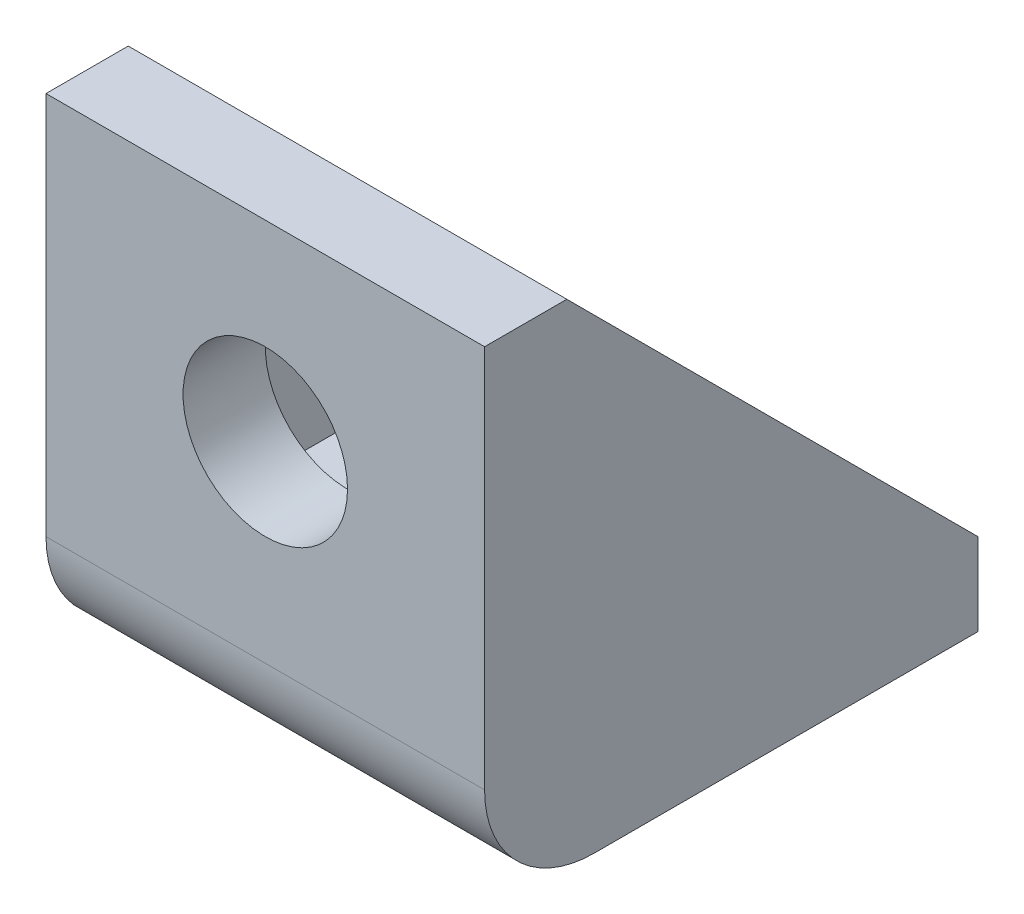
SolidWorks part; units mm, degrees
ref_plane "Front Plane" through (0, 0, 0) normal (0, 0, 1) x (1, 0, 0)
ref_plane "Top Plane" through (0, 0, 0) normal (0, 1, 0) x (1, 0, 0)
ref_plane "Right Plane" through (0, 0, 0) normal (1, 0, 0) x (0, 0, -1)
sketch "Sketch1" plane through (0, 0, 0) normal (1, 0, 0) x (0, 0, -1)
  line L1 (0, 0) -> (9, 0)
  line L2 (0, 0) -> (0, 1.6648)
  line L3 (1.5, 1.5) -> (9, 1.5)
  line L4 (9, 0) -> (9, 1.5)
  line L5 (0, 0) -> (1.7521, 0)
  line L6 (0, 0) -> (0, 9)
  line L7 (0, 9) -> (1.5, 9)
  line L8 (1.5, 1.5) -> (1.5, 9)
  dimension "D1" = 9
  dimension "D2" = 7.5
  dimension "D3" = 1.5
extrude "Boss-Extrude1" add sketch "Sketch1" along normal mid plane 8 contours L3 L8 L7 L6 L2 L1 L4
sketch "Sketch2" plane through (4, 0, 0) normal (1, 0, 0) x (0, 0, -1)
  line L0 (1.5, 9) -> (9, 1.5)
  line L1 (1.5, 1.5) -> (9, 1.5) construction
  line L2 (1.5, 1.5) -> (1.5, 9) construction
  line L3 (1.5, 1.5) -> (9, 1.5)
  line L4 (1.5, 1.5) -> (1.5, 9)
extrude "Boss-Extrude2" add sketch "Sketch2" against normal blind 0.5
mirror "Mirror1" about plane through (0, 0, 0) normal (1, 0, 0) of "Boss-Extrude2"
sketch "Sketch3" plane through (0, 0, 0) normal (0, 0, 1) x (1, 0, 0)
  line L0 (0, -4.95) -> (0, 4.95) construction
  line L2 (4.4, 0) -> (-4.4, 0) construction
  circle A0 centre (0, 5.5) radius 1.5
  dimension "D2" = 3
  dimension "D1" = 5.5
sketch "Sketch4" plane through (0, 0, 0) normal (0, -1, 0) x (1, 0, 0)
  line L0 (0, -4.95) -> (0, 4.95) construction
  line L1 (4, 0) -> (-4, 0) construction
  circle A0 centre (0, -5.5) radius 1.5
  dimension "D1" = 5.5
extrude "Cut-Extrude1" cut sketch "Sketch3" against normal through all
extrude "Cut-Extrude2" cut sketch "Sketch4" against normal through all contours A0
fillet "Fillet1" radius 2 1 edges at (0, 0, 0)
